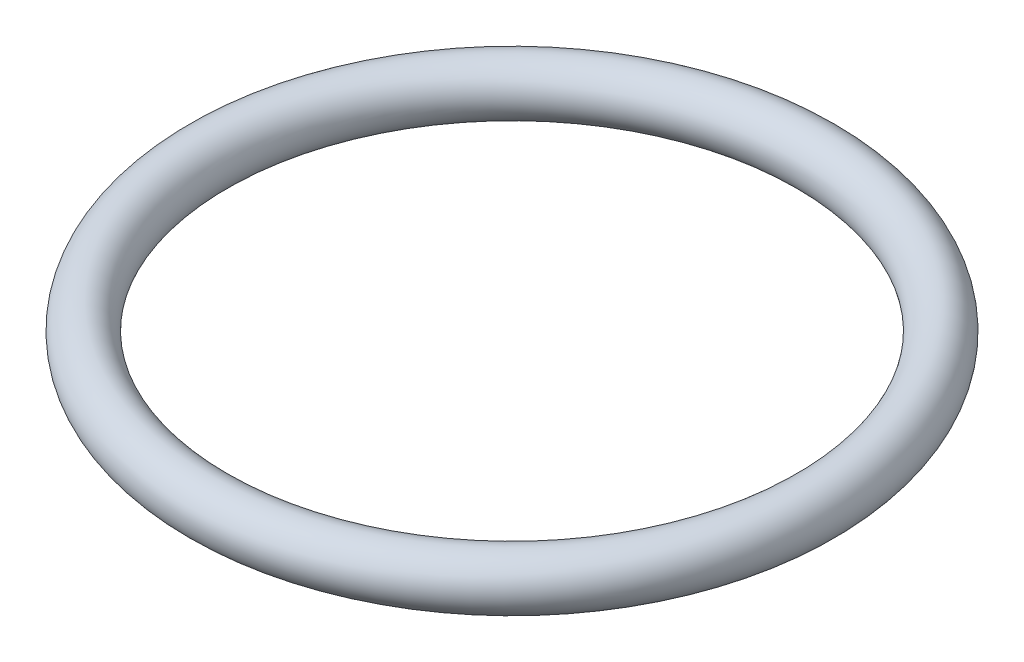
SolidWorks part; units mm, degrees
ref_plane "前视基准面" through (0, 0, 0) normal (0, 0, 1) x (1, 0, 0)
ref_plane "上视基准面" through (0, 0, 0) normal (0, 1, 0) x (1, 0, 0)
ref_plane "右视基准面" through (0, 0, 0) normal (1, 0, 0) x (0, 0, -1)
other "Configuration Table"
sketch "草图1" plane through (0, 0, 0) normal (0, 1, 0) x (1, 0, 0)
  circle A0 centre (0, 0) radius 6.9
  dimension "D1" = 13.8
sweep "扫描1" add path "草图1" circular profile diameter 1.2 parameters "D3"=1.2
